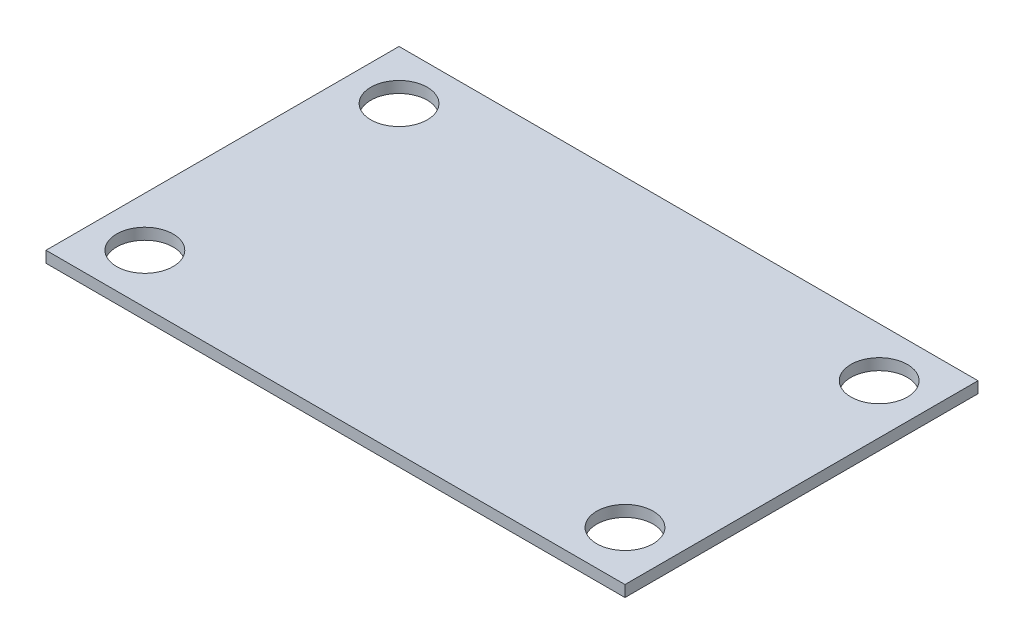
SolidWorks part; units mm, degrees
ref_plane "前视基准面" through (0, 0, 0) normal (0, 0, 1) x (1, 0, 0)
ref_plane "上视基准面" through (0, 0, 0) normal (0, 1, 0) x (1, 0, 0)
ref_plane "右视基准面" through (0, 0, 0) normal (1, 0, 0) x (0, 0, -1)
other "Configuration Table"
sketch "草图1" plane through (0, 0, 0) normal (0, 1, 0) x (1, 0, 0)
  line L0 (-41, 0) -> (46.2143, 0) construction
  line L1 (-41, 25) -> (41, 25)
  line L2 (-41, 25) -> (-41, -25)
  line L3 (-41, -25) -> (41, -25)
  line L4 (41, 25) -> (41, -25)
  line L7 (0, 25) -> (0, -30.3232) construction
  circle A2 centre (-34, -18) radius 4
  circle A3 centre (34, -18) radius 4
  circle A4 centre (34, 18) radius 4
  circle A5 centre (-34, 18) radius 4
  dimension "D3" = 7
  dimension "D4" = 8
  dimension "D1" = 50
  dimension "D2" = 82
  dimension "D5" = 7
extrude "凸台-拉伸1" add sketch "草图1" along normal blind 1.6
